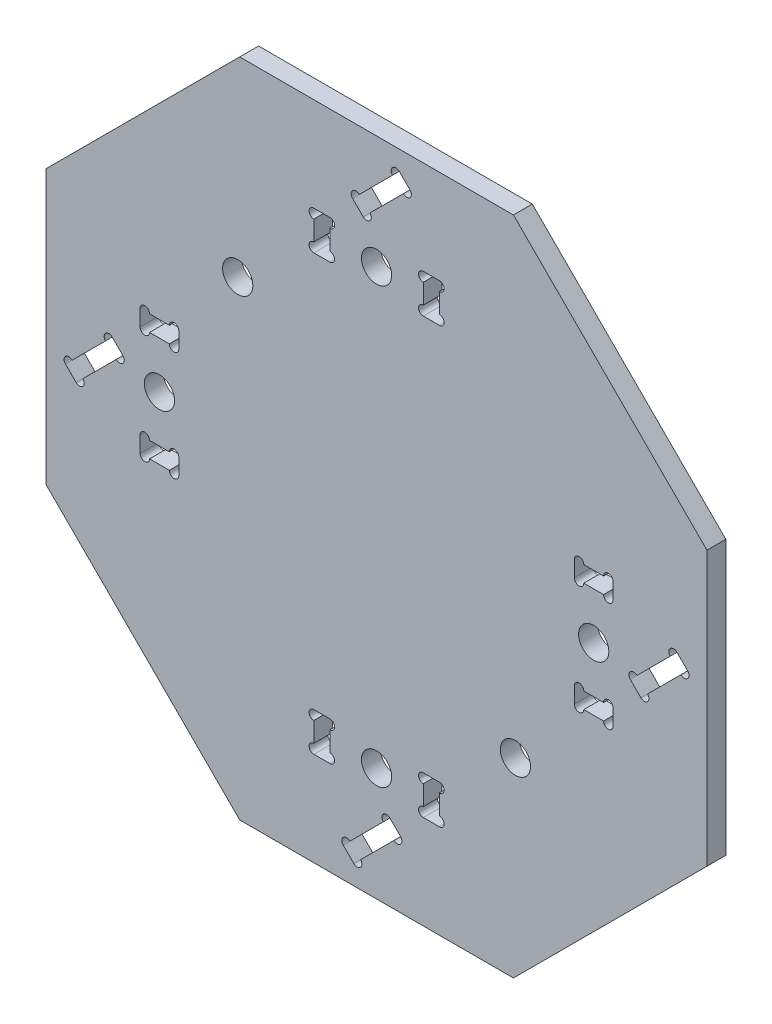
SolidWorks part; units mm, degrees
material "Thornel VCB-20 Carbon Cloth"
ref_plane "Front Plane" through (0, 0, 0) normal (0, 0, 1) x (1, 0, 0)
ref_plane "Top Plane" through (0, 0, 0) normal (0, 1, 0) x (1, 0, 0)
ref_plane "Right Plane" through (0, 0, 0) normal (1, 0, 0) x (0, 0, -1)
sketch "Sketch1" plane through (0, 0, 0) normal (0, 0, 1) x (1, 0, 0)
  line L1 (-14.4975, 35) -> (14.4975, 35)
  line L2 (-35, 14.4975) -> (-35, -14.4975)
  line L3 (-14.4975, -35) -> (14.4975, -35)
  line L4 (35, 14.4975) -> (35, -14.4975)
  line L5 (14.4975, 35) -> (35, 14.4975)
  line L6 (35, -14.4975) -> (14.4975, -35)
  line L14 (-20.95, 6.65) -> (-25.05, 6.65)
  line L15 (-25.05, 6.65) -> (-25.05, 4.95)
  line L16 (-25.05, 4.95) -> (-20.95, 4.95)
  line L17 (-20.95, 4.95) -> (-20.95, 6.65)
  line L18 (-20.95, 6.65) -> (-25.05, 6.65)
  line L19 (-25.05, 6.65) -> (-25.05, 4.95)
  line L20 (-25.05, 4.95) -> (-20.95, 4.95)
  line L21 (-20.95, 4.95) -> (-20.95, 6.65)
  line L22 (6.65, 20.95) -> (6.65, 25.05)
  line L23 (6.65, 25.05) -> (4.95, 25.05)
  line L24 (4.95, 25.05) -> (4.95, 20.95)
  line L25 (4.95, 20.95) -> (6.65, 20.95)
  line L26 (-20.95, -4.95) -> (-25.05, -4.95)
  line L27 (-25.05, -4.95) -> (-25.05, -6.65)
  line L28 (-25.05, -6.65) -> (-20.95, -6.65)
  line L29 (-20.95, -6.65) -> (-20.95, -4.95)
  line L30 (-20.95, -4.95) -> (-25.05, -4.95)
  line L31 (-25.05, -4.95) -> (-25.05, -6.65)
  line L32 (-25.05, -6.65) -> (-20.95, -6.65)
  line L33 (-20.95, -6.65) -> (-20.95, -4.95)
  line L34 (-4.95, 20.95) -> (-4.95, 25.05)
  line L35 (-4.95, 25.05) -> (-6.65, 25.05)
  line L36 (-6.65, 25.05) -> (-6.65, 20.95)
  line L37 (-6.65, 20.95) -> (-4.95, 20.95)
  line L38 (20.95, -6.65) -> (25.05, -6.65)
  line L39 (25.05, -6.65) -> (25.05, -4.95)
  line L40 (25.05, -4.95) -> (20.95, -4.95)
  line L41 (20.95, -4.95) -> (20.95, -6.65)
  line L42 (20.95, 4.95) -> (25.05, 4.95)
  line L43 (25.05, 4.95) -> (25.05, 6.65)
  line L44 (25.05, 6.65) -> (20.95, 6.65)
  line L45 (20.95, 6.65) -> (20.95, 4.95)
  line L46 (-6.65, -20.95) -> (-6.65, -25.05)
  line L47 (-6.65, -25.05) -> (-4.95, -25.05)
  line L48 (-4.95, -25.05) -> (-4.95, -20.95)
  line L49 (-4.95, -20.95) -> (-6.65, -20.95)
  line L50 (4.95, -20.95) -> (4.95, -25.05)
  line L51 (4.95, -25.05) -> (6.65, -25.05)
  line L52 (6.65, -25.05) -> (6.65, -20.95)
  line L53 (6.65, -20.95) -> (4.95, -20.95)
  line L102 (-35, 14.4975) -> (-14.4975, 35)
  line L103 (-14.4975, -35) -> (-35, -14.4975)
  circle A0 centre (0, 0) radius 35 construction
  point P40 (0, 0)
  point P49 (0, 0)
  dimension "D1" = 70
  dimension "D6" = 45
  dimension "D2" = 0.05
  dimension "D3" = 0.05
  dimension "D4" = 4
  dimension "D5" = 4
extrude "Boss-Extrude1" add sketch "Sketch1" along normal blind 2
sketch "Sketch2" plane through (0, 0, 2) normal (0, 0, 1) x (1, 0, 0)
  line L0 (-20.95, 4.95) -> (-25.05, -4.95) construction
  circle A0 centre (-23, 0) radius 1.6
  circle A1 centre (0, 23) radius 1.6
  circle A2 centre (23, 0) radius 1.6
  circle A3 centre (0, -23) radius 1.6
  point P11 (0, 0)
  dimension "D2" = 3.2
  dimension "D1" = 4
extrude "Cut-Extrude1" cut sketch "Sketch2" against normal up to next
sketch "Sketch3" plane through (0, 0, 2) normal (0, 0, 1) x (1, 0, 0)
  line L0 (-6.6875, 6.6875) -> (0, 0) construction
  line L1 (-32.2441, -1.6971) -> (-28.7085, 1.8385)
  line L2 (-28.0014, 2.5456) -> (-26.8701, 1.4142)
  line L3 (-27.5772, 0.7071) -> (-31.1127, -2.8284)
  line L4 (-31.8198, -3.5355) -> (-32.9512, -2.4042)
  line L5 (0, 0) -> (-13.8965, -13.8965) construction
  line L6 (-3.5355, -31.8198) -> (-2.4042, -32.9512)
  line L7 (0.7071, -27.5772) -> (-2.8284, -31.1127)
  line L8 (2.5456, -28.0014) -> (1.4142, -26.8701)
  line L9 (-1.6971, -32.2441) -> (1.8385, -28.7085)
  line L10 (32.2441, 1.6971) -> (28.7085, -1.8385)
  line L11 (28.0014, -2.5456) -> (26.8701, -1.4142)
  line L12 (27.5772, -0.7071) -> (31.1127, 2.8284)
  line L13 (31.8198, 3.5355) -> (32.9512, 2.4042)
  line L14 (0, 0) -> (-11.5471, 0) construction
  line L15 (3.5355, 31.8198) -> (2.4042, 32.9512)
  line L16 (-0.7071, 27.5772) -> (2.8284, 31.1127)
  line L17 (-2.5456, 28.0014) -> (-1.4142, 26.8701)
  line L18 (1.6971, 32.2441) -> (-1.8385, 28.7085)
  arc A0 (-32.2441, -1.6971) -> (-32.9512, -2.4042) centre (-32.5976, -2.0506) ccw
  arc A1 (-31.8198, -3.5355) -> (-31.1127, -2.8284) centre (-31.4663, -3.182) ccw
  arc A2 (-28.0014, 2.5456) -> (-28.7085, 1.8385) centre (-28.355, 2.192) ccw
  arc A3 (-27.5772, 0.7071) -> (-26.8701, 1.4142) centre (-27.2236, 1.0607) ccw
  arc A4 (0.7071, -27.5772) -> (1.4142, -26.8701) centre (1.0607, -27.2236) cw
  arc A5 (2.5456, -28.0014) -> (1.8385, -28.7085) centre (2.192, -28.355) cw
  arc A6 (-3.5355, -31.8198) -> (-2.8284, -31.1127) centre (-3.182, -31.4663) cw
  arc A7 (-1.6971, -32.2441) -> (-2.4042, -32.9512) centre (-2.0506, -32.5976) cw
  arc A8 (32.2441, 1.6971) -> (32.9512, 2.4042) centre (32.5976, 2.0506) ccw
  arc A9 (31.8198, 3.5355) -> (31.1127, 2.8284) centre (31.4663, 3.182) ccw
  arc A10 (28.0014, -2.5456) -> (28.7085, -1.8385) centre (28.355, -2.192) ccw
  arc A11 (27.5772, -0.7071) -> (26.8701, -1.4142) centre (27.2236, -1.0607) ccw
  arc A12 (-0.7071, 27.5772) -> (-1.4142, 26.8701) centre (-1.0607, 27.2236) cw
  arc A13 (-2.5456, 28.0014) -> (-1.8385, 28.7085) centre (-2.192, 28.355) cw
  arc A14 (3.5355, 31.8198) -> (2.8284, 31.1127) centre (3.182, 31.4663) cw
  arc A15 (1.6971, 32.2441) -> (2.4042, 32.9512) centre (2.0506, 32.5976) cw
  dimension "D3" = 0.5
  dimension "D1" = 1.6
  dimension "D2" = 7
  dimension "D4" = 45
  dimension "D5" = 40
  dimension "D6" = 43
extrude "Cut-Extrude2" cut sketch "Sketch3" against normal up to next
sketch "Sketch4" plane through (0, 0, 2) normal (0, 0, 1) x (1, 0, 0)
  line L0 (-20.95, 6.65) -> (-25.05, 6.65) construction
  line L1 (-25.05, 4.95) -> (-20.95, 4.95) construction
  line L2 (-15.8437, 0) -> (-10.7505, 0) construction
  circle A0 centre (-24.55, 6.65) radius 0.5
  circle A1 centre (-24.55, 4.95) radius 0.5
  circle A2 centre (-21.45, 6.65) radius 0.5
  circle A3 centre (-21.45, 4.95) radius 0.5
  circle A4 centre (-21.45, -4.95) radius 0.5
  circle A5 centre (-21.45, -6.65) radius 0.5
  circle A6 centre (-24.55, -4.95) radius 0.5
  circle A7 centre (-24.55, -6.65) radius 0.5
  circle A8 centre (6.65, 24.55) radius 0.5
  circle A9 centre (4.95, 24.55) radius 0.5
  circle A10 centre (6.65, 21.45) radius 0.5
  circle A11 centre (4.95, 21.45) radius 0.5
  circle A12 centre (-4.95, 21.45) radius 0.5
  circle A13 centre (-6.65, 21.45) radius 0.5
  circle A14 centre (-4.95, 24.55) radius 0.5
  circle A15 centre (-6.65, 24.55) radius 0.5
  circle A16 centre (24.55, -6.65) radius 0.5
  circle A17 centre (24.55, -4.95) radius 0.5
  circle A18 centre (21.45, -6.65) radius 0.5
  circle A19 centre (21.45, -4.95) radius 0.5
  circle A20 centre (21.45, 4.95) radius 0.5
  circle A21 centre (21.45, 6.65) radius 0.5
  circle A22 centre (24.55, 4.95) radius 0.5
  circle A23 centre (24.55, 6.65) radius 0.5
  circle A24 centre (-6.65, -24.55) radius 0.5
  circle A25 centre (-4.95, -24.55) radius 0.5
  circle A26 centre (-6.65, -21.45) radius 0.5
  circle A27 centre (-4.95, -21.45) radius 0.5
  circle A28 centre (4.95, -21.45) radius 0.5
  circle A29 centre (6.65, -21.45) radius 0.5
  circle A30 centre (4.95, -24.55) radius 0.5
  circle A31 centre (6.65, -24.55) radius 0.5
  point P77 (0, 0)
  dimension "D1" = 1
  dimension "D2" = 4
extrude "Cut-Extrude3" cut sketch "Sketch4" against normal up to next (2 mm away)
sketch "Sketch5" plane through (0, 0, 2) normal (0, 0, 1) x (1, 0, 0)
  line L0 (-27.4357, 1.9799) -> (-1.9799, 27.4357) construction
  line L1 (-26.8701, 1.4142) -> (-28.0014, 2.5456) construction
  line L2 (-2.5456, 28.0014) -> (-1.4142, 26.8701) construction
  line L3 (1.9799, -27.4357) -> (27.4357, -1.9799) construction
  line L4 (2.5456, -28.0014) -> (1.4142, -26.8701) construction
  line L5 (26.8701, -1.4142) -> (28.0014, -2.5456) construction
  circle A0 centre (-14.7078, 14.7078) radius 1.6
  circle A1 centre (14.7078, -14.7078) radius 1.6
  dimension "D1" = 3.2
extrude "Cut-Extrude4" cut sketch "Sketch5" against normal up to next
